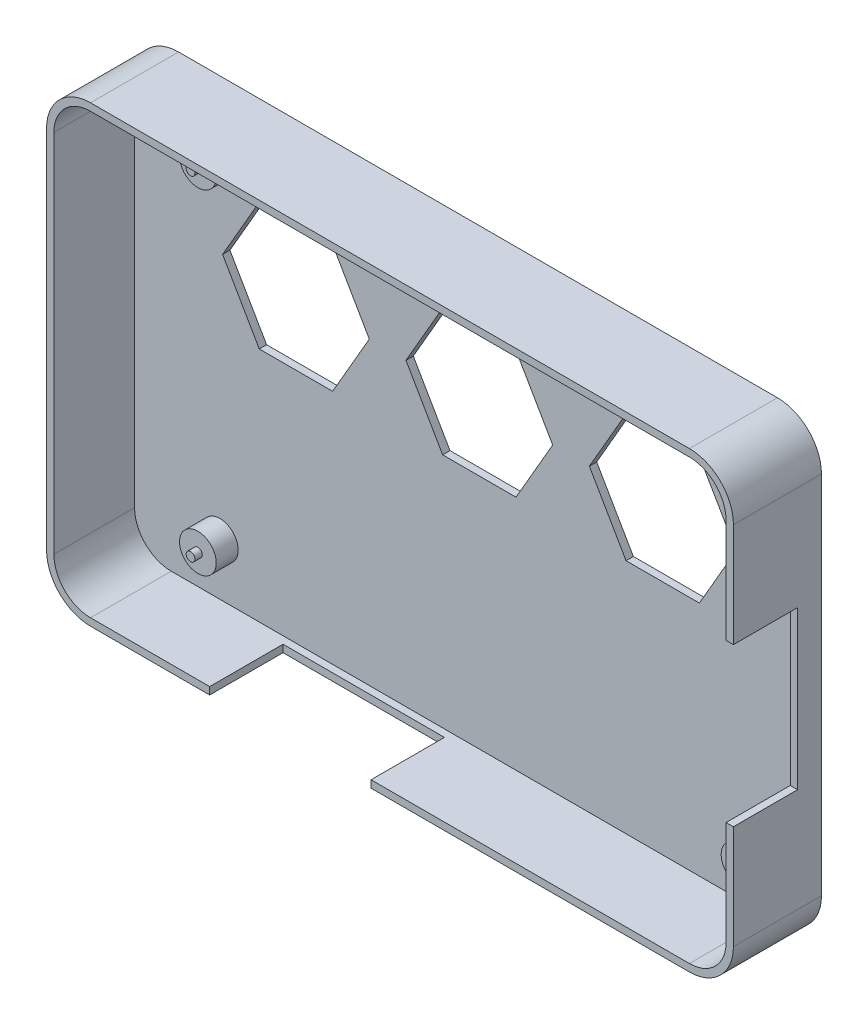
SolidWorks part; units mm, degrees
ref_plane "Ebene vorne" through (0, 0, 0) normal (1, 0, 0) x (0, 1, 0)
ref_plane "Ebene oben" through (0, 0, 0) normal (0, 0, 1) x (0, 1, 0)
ref_plane "Ebene rechts" through (0, 0, 0) normal (0, 1, 0) x (-1, 0, 0)
sketch "Skizze1" plane through (0, 0, 0) normal (0, 0, 1) x (0, 1, 0)
  line L0 (-30.9, -46.82) -> (30.9, -46.82)
  line L1 (-30.9, -46.82) -> (-30.9, 46.82)
  line L2 (-30.9, 46.82) -> (30.9, 46.82)
  line L3 (30.9, -46.82) -> (30.9, 46.82)
  line L4 (-30.9, -46.82) -> (30.9, 46.82) construction
  line L5 (-30.9, 46.82) -> (30.9, -46.82) construction
  point P0 (0, 0)
  dimension "D1" = 61.8
  dimension "D2" = 93.64
extrude "Aufsatz-Linear austragen1" add sketch "Skizze1" along normal blind 12
fillet "Verrundung1" radius 6 4 edges at (46.82, -30.9, 6) (-46.82, -30.9, 6) (-46.82, 30.9, 6) (46.82, 30.9, 6)
shell "Wandung1" thickness 1
sketch "Skizze2" plane through (46.82, 0, 0) normal (1, 0, 0) x (0, 1, 0)
  line L0 (-24.9, 12) -> (24.9, 12) construction
  line L1 (-10.75, 20.75) -> (10.75, 20.75)
  line L2 (-10.75, 20.75) -> (-10.75, 3.25)
  line L3 (-10.75, 3.25) -> (10.75, 3.25)
  line L4 (10.75, 20.75) -> (10.75, 3.25)
  line L5 (-10.75, 20.75) -> (10.75, 3.25) construction
  line L6 (-10.75, 3.25) -> (10.75, 20.75) construction
  line L7 (-24.9, 0) -> (24.9, 0) construction
  point P0 (0, 12)
  dimension "D1" = 21.5
  dimension "D2" = 17.5
  dimension "D3" = 3.25
extrude "Schnitt-Linear austragen1" cut sketch "Skizze2" against normal blind 6
sketch "Skizze3" plane through (0, -30.9, 0) normal (0, -1, 0) x (1, 0, 0)
  line L0 (-40.82, 12) -> (40.82, 12) construction
  line L1 (-2.58, 12) -> (-24.58, 12)
  line L2 (-2.58, 12) -> (-2.58, 2)
  line L3 (-2.58, 2) -> (-24.58, 2)
  line L4 (-24.58, 12) -> (-24.58, 2)
  line L5 (-40.82, 0) -> (40.82, 0) construction
  dimension "D1" = 22
  dimension "D2" = 10
  dimension "D3" = 43.4
  dimension "D4" = 2
extrude "Schnitt-Linear austragen2" cut sketch "Skizze3" against normal blind 6
sketch "Skizze4" plane through (0, 0, 0) normal (0, 0, -1) x (1, 0, 0)
  line L0 (-33.82, 30.9) -> (-33.82, -30.9) construction
  line L2 (-18.82, -2.3397) -> (-28.82, -2.3397)
  line L3 (-28.82, -2.3397) -> (-33.82, -11)
  line L4 (-33.82, -11) -> (-28.82, -19.6603)
  line L5 (-28.82, -19.6603) -> (-18.82, -19.6603)
  line L6 (-18.82, -19.6603) -> (-13.82, -11)
  line L7 (-13.82, -11) -> (-18.82, -2.3397)
  line L14 (-46.82, -24.9) -> (-46.82, 24.9) construction
  line L15 (-40.82, 30.9) -> (40.82, 30.9) construction
  circle A8 centre (-23.82, -11) radius 8.6603 construction
  point P3 (-33.82, 0)
  dimension "D3" = 41.9
  dimension "D5" = 13
  dimension "D1" = 10
  dimension "D2" = 30.9
extrude "Schnitt-Linear austragen4" cut sketch "Skizze4" against normal blind 6
pattern_linear "Lineares Muster1" count 3 spacing 25 along (1, 0, 0) of "Schnitt-Linear austragen4"
sketch "Skizze5" plane through (0, 0, 1) normal (0, 0, 1) x (1, 0, 0)
  line L0 (40.82, 30.9) -> (-40.82, 30.9) construction
  line L1 (-46.82, 24.9) -> (-46.82, -24.9) construction
  line L2 (46.82, 10.75) -> (46.82, 24.9) construction
  line L3 (-2.58, -30.9) -> (40.82, -30.9) construction
  line L4 (46.82, -24.9) -> (46.82, -10.75) construction
  line L5 (-40.82, -30.9) -> (-24.58, -30.9) construction
  circle A0 centre (-34.19, 22.7) radius 2.5
  circle A1 centre (39.65, 22.7) radius 2.5
  circle A2 centre (39.65, -22.86) radius 2.5
  circle A3 centre (-34.19, -22.86) radius 2.5
  dimension "D1" = 8.2
  dimension "D2" = 12.63
  dimension "D3" = 5
  dimension "D4" = 73.84
  dimension "D5" = 7.17
  dimension "D6" = 8.2
  dimension "D7" = 5
  dimension "D8" = 45.56
  dimension "D9" = 5
  dimension "D10" = 8.04
  dimension "D11" = 7.17
  dimension "D12" = 5
  dimension "D13" = 8.04
  dimension "D14" = 73.84
  dimension "D15" = 45.56
  dimension "D16" = 12.63
extrude "Aufsatz-Linear austragen2" add sketch "Skizze5" along normal blind 3
sketch "Skizze6" plane through (0, 0, 4) normal (0, 0, 1) x (1, 0, 0)
  circle A0 centre (-34.19, 22.7) radius 0.6
  circle A1 centre (-34.19, -22.86) radius 0.6
  circle A2 centre (39.65, -22.86) radius 0.6
  circle A3 centre (39.65, 22.7) radius 0.6
  dimension "D1" = 1.2
  dimension "D2" = 1.2
  dimension "D3" = 1.2
  dimension "D4" = 1.2
extrude "Aufsatz-Linear austragen3" add sketch "Skizze6" along normal blind 1
